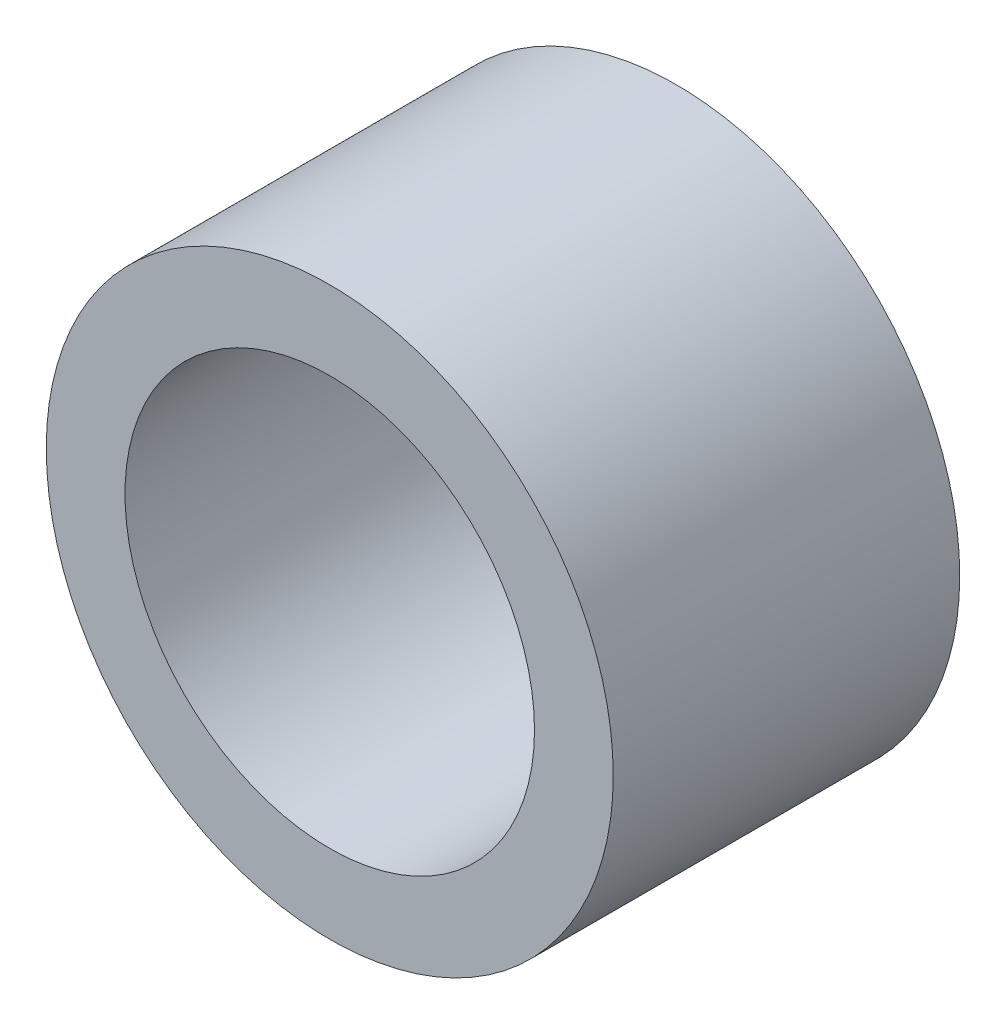
SolidWorks part; units mm, degrees
ref_plane "正面" through (0, 0, 0) normal (0, 0, 1) x (1, 0, 0)
ref_plane "平面" through (0, 0, 0) normal (0, 1, 0) x (1, 0, 0)
ref_plane "右側面" through (0, 0, 0) normal (1, 0, 0) x (0, 0, -1)
sketch "ｽｹｯﾁ1" plane through (0, 0, 0) normal (0, 0, 1) x (1, 0, 0)
  circle A0 centre (0, 0) radius 4.5
  circle A1 centre (0, 0) radius 3.25
  dimension "D1" = 6.5
  dimension "D2" = 9
extrude "ﾎﾞｽ - 押し出し1" add sketch "ｽｹｯﾁ1" along normal blind 5.5
